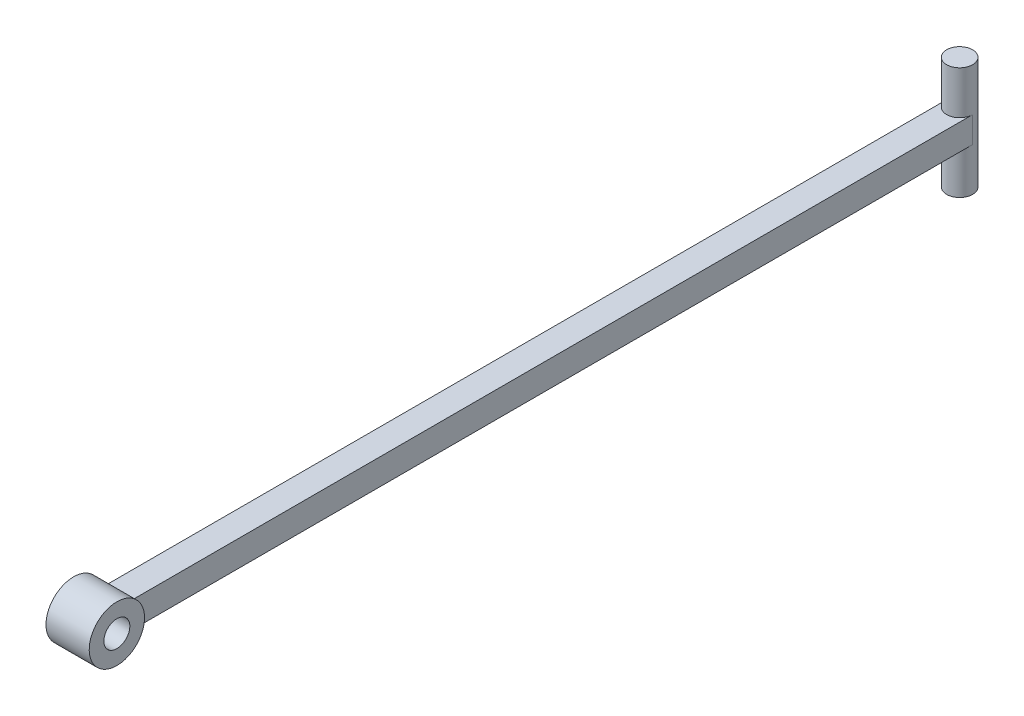
SolidWorks part; units mm, degrees
ref_plane "Front Plane" through (0, 0, 0) normal (0, 0, 1) x (1, 0, 0)
ref_plane "Top Plane" through (0, 0, 0) normal (0, 1, 0) x (1, 0, 0)
ref_plane "Right Plane" through (0, 0, 0) normal (1, 0, 0) x (0, 0, -1)
sketch "Sketch1" plane through (0, 0, 0) normal (0, 0, 1) x (1, 0, 0)
  line L1 (0, 0) -> (60, 0)
  line L2 (0, 0) -> (0, -60)
  line L3 (0, -60) -> (60, -60)
  line L4 (60, 0) -> (60, -60)
  dimension "D1" = 60
  dimension "D2" = 60
extrude "Boss-Extrude1" add sketch "Sketch1" along normal blind 2000
sketch "Sketch2" plane through (0, 0, 0) normal (0, 1, 0) x (1, 0, 0)
  line L0 (60, 0) -> (0, 0) construction
  circle A0 centre (30, 0) radius 30
extrude "Boss-Extrude2" add sketch "Sketch2" along normal blind 100 and the other way blind 160
sketch "Sketch3" plane through (60, 0, 0) normal (1, 0, 0) x (0, 0, -1)
  line L0 (-2000, -60) -> (-2000, 0) construction
  circle A0 centre (-2000, -30) radius 64
  circle A1 centre (-2000, -30) radius 30
  dimension "D1" = 128
extrude "Boss-Extrude3" add sketch "Sketch3" along normal blind 20 and the other way blind 80
sketch "Sketch4" plane through (80, 0, 0) normal (1, 0, 0) x (0, 0, -1)
  circle A0 centre (-2000, -30) radius 30
extrude "Cut-Extrude1" cut sketch "Sketch4" against normal blind 360
